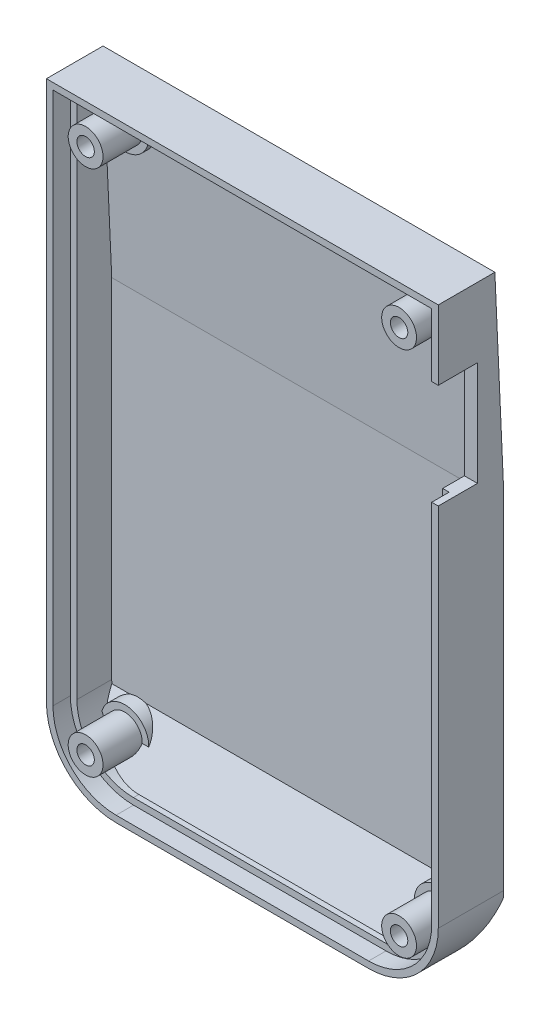
SolidWorks part; units mm, degrees
ref_plane "前视基准面" through (0, 0, 0) normal (0, 0, 1) x (1, 0, 0)
ref_plane "上视基准面" through (0, 0, 0) normal (0, 1, 0) x (1, 0, 0)
ref_plane "右视基准面" through (0, 0, 0) normal (1, 0, 0) x (0, 0, -1)
sketch "草图1" plane through (0, 0, 0) normal (0, 0, 1) x (1, 0, 0)
  line L1 (-45, 70) -> (0, 70)
  line L2 (-45, 70) -> (-45, 8)
  line L3 (-37, 0) -> (-8, 0)
  line L4 (0, 70) -> (0, 8)
  arc A0 (-8, 0) -> (0, 8) centre (-8, 8) ccw
  arc A1 (-45, 8) -> (-37, 0) centre (-37, 8) ccw
  point P4 (0, 0)
  point P8 (0, 0)
  point P11 (-45, 0)
  dimension "D3" = 8
  dimension "D1" = 45
  dimension "D2" = 70
extrude "凸台-拉伸1" add sketch "草图1" along normal blind 7.5 contours L1 L4 A0 L3 A1 L2
sketch "草图2" plane through (0, 0, 0) normal (1, 0, 0) x (0, 0, -1)
  line L0 (0, 0) -> (0, 7.2)
  line L1 (0, 0) -> (0, 8) construction
  line L2 (0, 7.2) -> (-4, 0)
  line L3 (-7.5, 0) -> (0, 0) construction
  line L4 (-4, 0) -> (0, 0)
  line L5 (0, 70) -> (-1, 70)
  line L6 (-7.5, 70) -> (0, 70) construction
  line L7 (-1, 70) -> (0, 48)
  line L8 (0, 70) -> (0, 8) construction
  line L9 (0, 48) -> (0, 70)
  dimension "D1" = 4
  dimension "D2" = 7.2
  dimension "D3" = 22
  dimension "D4" = 1
extrude "切除-拉伸1" cut sketch "草图2" against normal through all
shell "抽壳1" thickness 1.5
sketch "草图3" plane through (0, 0, 7.5) normal (0, 0, 1) x (1, 0, 0)
  line L0 (-37, 1.5) -> (-8, 1.5) construction
  line L1 (-43.5, 68.5) -> (-1.5, 68.5)
  line L2 (-43.5, 68.5) -> (-43.5, 8)
  line L3 (-37, 1.5) -> (-8, 1.5)
  line L4 (-1.5, 68.5) -> (-1.5, 8)
  line L5 (-1.5, 68.5) -> (-1.5, 8) construction
  line L6 (-44.25, 69.25) -> (-0.75, 69.25)
  line L7 (-0.75, 69.25) -> (-0.75, 8)
  line L8 (-37, 0.75) -> (-8, 0.75)
  line L9 (-44.25, 69.25) -> (-44.25, 8)
  arc A0 (-8, 1.5) -> (-1.5, 8) centre (-8, 8) ccw
  arc A1 (-43.5, 8) -> (-37, 1.5) centre (-37, 8) ccw
  arc A2 (-8, 0.75) -> (-0.75, 8) centre (-8, 8) ccw
  arc A3 (-44.25, 8) -> (-37, 0.75) centre (-37, 8) ccw
  dimension "D1" = 6.5
  dimension "D2" = 0.75
extrude "切除-拉伸2" cut sketch "草图3" against normal blind 2
sketch "草图4" plane through (0, 0, 1.5) normal (0, 0, 1) x (1, 0, 0)
  line L0 (-45, 70) -> (-45, 8) construction
  line L1 (-45, 70) -> (0, 70) construction
  line L2 (-22.5, -924.2136) -> (-22.5, 49075.7864) construction
  line L3 (-45, 48) -> (-45, 8) construction
  line L4 (0, 48) -> (0, 8) construction
  circle A0 centre (-40.5, 65.5) radius 2.75
  circle A1 centre (-40.5, 5) radius 2.75
  circle A2 centre (-4.5, 5) radius 2.75
  circle A3 centre (-4.5, 65.5) radius 2.75
  dimension "D3" = 5.5
  dimension "D1" = 4.5
  dimension "D2" = 4.5
  dimension "D5" = 60.5
  dimension "D4" = 2
extrude "凸台-拉伸2" add sketch "草图4" along normal blind 1.5
sketch "草图5" plane through (0, 0, 3) normal (0, 0, 1) x (1, 0, 0)
  circle A0 centre (-40.5, 65.5) radius 2
  circle A1 centre (-4.5, 65.5) radius 2
  circle A2 centre (-40.5, 5) radius 2
  circle A3 centre (-4.5, 5) radius 2
  arc A4 (-1.8757, 5.8221) -> (-7.2477, 4.8887) centre (-4.5, 5) ccw construction
  point P11 (0, 0)
  dimension "D1" = 4
extrude "凸台-拉伸3" add sketch "草图5" along normal blind 4.5
sketch "草图6" plane through (0, 0, 0) normal (0, 0, -1) x (-1, 0, 0)
  circle A0 centre (4.5, 65.5) radius 1.75
  circle A1 centre (40.5, 65.5) radius 1.75
  circle A2 centre (40.5, 5) radius 1.75
  circle A3 centre (4.5, 5) radius 1.75
  circle A4 centre (4.5, 65.5) radius 2.75 construction
  circle A5 centre (40.5, 65.5) radius 2.75 construction
  arc A6 (43.1243, 5.8221) -> (37.7523, 4.8887) centre (40.5, 5) ccw construction
  arc A7 (7.2477, 4.8887) -> (1.8757, 5.8221) centre (4.5, 5) ccw construction
  dimension "D1" = 3.5
extrude "切除-拉伸3" cut sketch "草图6" against normal blind 2
sketch "草图9" plane through (0, 0, 0) normal (0, 0, 1) x (1, 0, 0)
  circle A0 centre (-40.5, 65.5) radius 1
  circle A1 centre (-4.5, 65.5) radius 1
  circle A2 centre (-4.5, 5) radius 1
  circle A3 centre (-40.5, 5) radius 1
  circle A8 centre (-4.5, 65.5) radius 1.75 construction
  circle A9 centre (-40.5, 65.5) radius 1.75 construction
  arc A10 (-38.8229, 4.5) -> (-42.1771, 4.5) centre (-40.5, 5) ccw construction
  arc A11 (-2.8229, 4.5) -> (-6.1771, 4.5) centre (-4.5, 5) ccw construction
  dimension "D1" = 2
extrude "切除-拉伸4" cut sketch "草图9" along normal through all
sketch "草图11" plane through (0, 0, 0) normal (1, 0, 0) x (0, 0, -1)
  line L0 (0, 0) -> (0, 7.2)
  line L2 (0, 7.2) -> (-4, 0)
  line L4 (-4, 0) -> (0, 0)
  line L5 (0, 70) -> (-1, 70)
  line L7 (-1, 70) -> (0, 48)
  line L9 (0, 48) -> (0, 70)
  line L10 (-7.5, 0) -> (-4, 0) construction
  line L11 (0, 48) -> (0, 8) construction
  line L12 (-7.5, 70) -> (-1, 70) construction
  dimension "D1" = 4
  dimension "D2" = 7.2
  dimension "D3" = 22
  dimension "D4" = 1
extrude "切除-拉伸5" cut sketch "草图11" against normal through all
sketch "草图12" plane through (0, 0, 7.5) normal (0, 0, 1) x (1, 0, 0)
  line L0 (0, 70) -> (0, 8) construction
  line L1 (0, 62) -> (-1.5, 62)
  line L2 (0, 62) -> (0, 50)
  line L3 (0, 50) -> (-1.5, 50)
  line L4 (-1.5, 62) -> (-1.5, 50)
  line L5 (-1.5, 8) -> (-1.5, 68.5) construction
  line L6 (-45, 70) -> (0, 70) construction
  dimension "D1" = 8
  dimension "D2" = 12
extrude "切除-拉伸6" cut sketch "草图12" against normal blind 4.5
